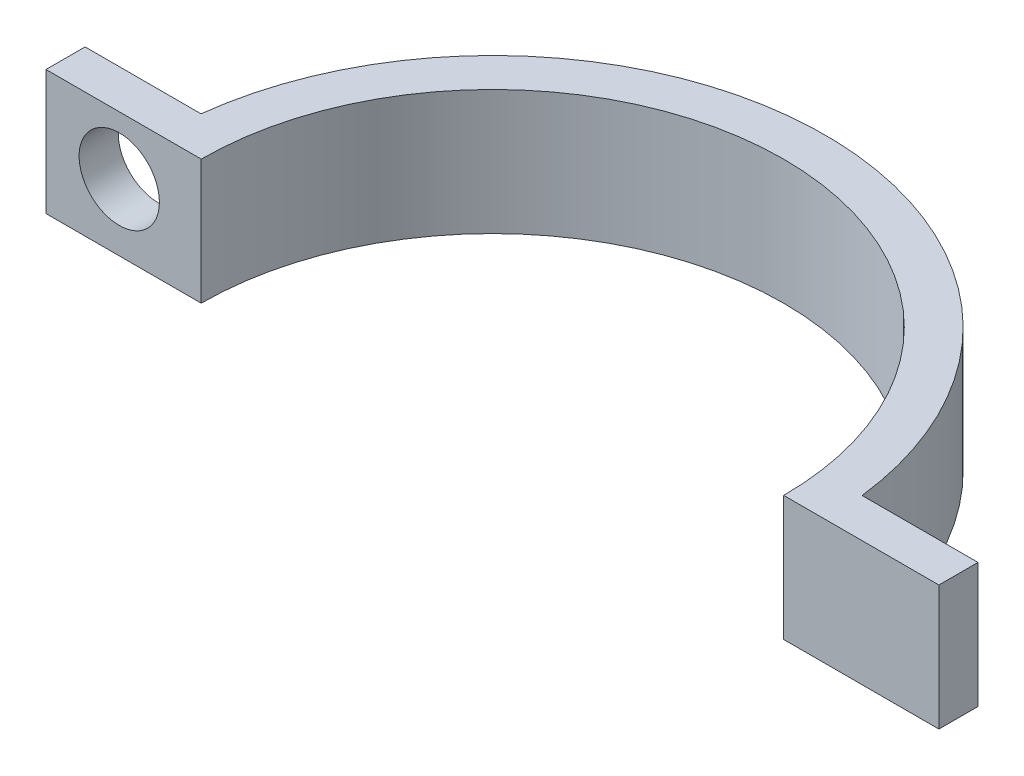
SolidWorks part; units mm, degrees
ref_plane "Front Plane" through (0, 0, 0) normal (0, 0, 1) x (1, 0, 0)
ref_plane "Top Plane" through (0, 0, 0) normal (0, 1, 0) x (1, 0, 0)
ref_plane "Right Plane" through (0, 0, 0) normal (1, 0, 0) x (0, 0, -1)
sketch "Sketch1" plane through (0, 0, 0) normal (0, 1, 0) x (1, 0, 0)
  line L0 (5.3655, 0) -> (3.5, 0)
  line L1 (5.3655, 0) -> (5.3655, 0.4699)
  line L2 (5.3655, 0.4699) -> (3.9723, 0.4699)
  line L5 (-5.3655, 0.4699) -> (-3.9723, 0.4699)
  line L6 (-5.3655, 0) -> (-5.3655, 0.4699)
  line L7 (-5.3655, 0) -> (-3.5, 0)
  arc A0 (3.5, 0) -> (-3.5, 0) centre (0, 0) ccw
  arc A1 (3.9723, 0.4699) -> (-3.9723, 0.4699) centre (0, 0) ccw
  dimension "D1" = 1.3932
extrude "Boss-Extrude1" add sketch "Sketch1" along normal blind 1.5
sketch "Sketch3" plane through (0, 0, 0) normal (0, 0, 1) x (1, 0, 0)
  circle A0 centre (-4.4852, 0.7988) radius 0.4824
extrude "Cut-Extrude1" cut sketch "Sketch3" against normal blind 0.47
